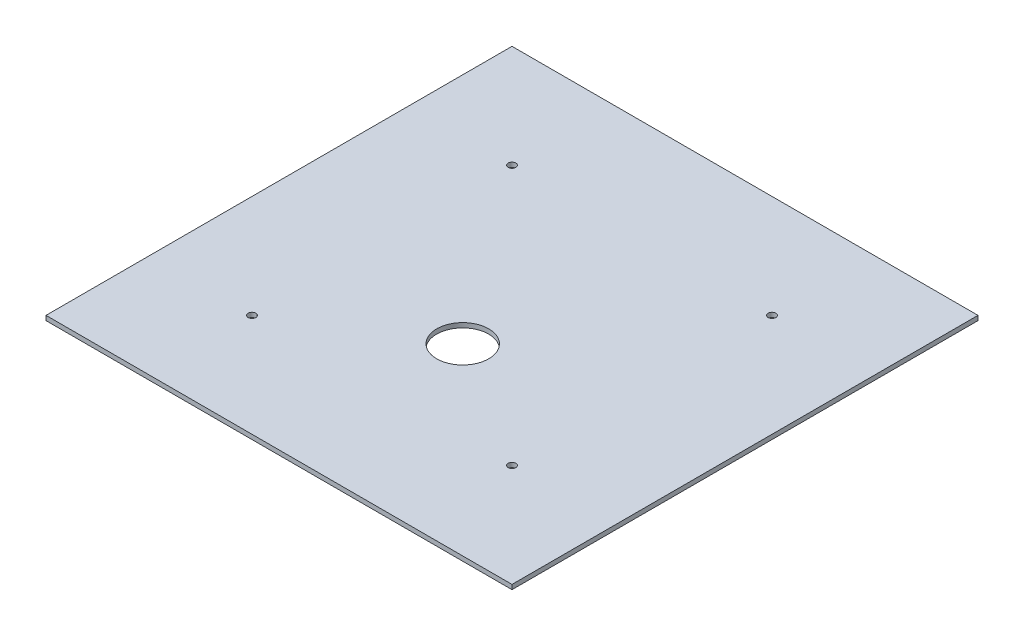
SolidWorks part; units mm, degrees
material "MDF"
ref_plane "Front Plane" through (0, 0, 0) normal (0, 0, 1) x (1, 0, 0)
ref_plane "Top Plane" through (0, 0, 0) normal (0, 1, 0) x (1, 0, 0)
ref_plane "Right Plane" through (0, 0, 0) normal (1, 0, 0) x (0, 0, -1)
sketch "Sketch2" plane through (0, 0, 0) normal (0, 1, 0) x (1, 0, 0)
  line L1 (-152.4, -152.4) -> (152.4, -152.4)
  line L2 (-152.4, -152.4) -> (-152.4, 152.4)
  line L3 (-152.4, 152.4) -> (152.4, 152.4)
  line L4 (152.4, -152.4) -> (152.4, 152.4)
  line L5 (-152.4, -152.4) -> (152.4, 152.4) construction
  line L6 (-152.4, 152.4) -> (152.4, -152.4) construction
  point P0 (0, 0)
  dimension "D1" = 304.8
  dimension "D2" = 304.8
extrude "Boss-Extrude1" add sketch "Sketch2" along normal blind 3
sketch "Sketch3" plane through (0, 3, 0) normal (0, 1, 0) x (1, 0, 0)
  line L0 (-85.035, 85.035) -> (85.035, 85.035) construction
  line L1 (85.035, 85.035) -> (85.035, -85.035) construction
  line L2 (85.035, -85.035) -> (-85.035, -85.035) construction
  line L3 (-85.035, -85.035) -> (-85.035, 85.035) construction
  line L4 (152.4, 152.4) -> (-152.4, 152.4) construction
  line L5 (152.4, -152.4) -> (152.4, 152.4) construction
  circle A4 centre (-85.035, 85.035) radius 2.5
  circle A5 centre (85.035, 85.035) radius 2.5
  circle A6 centre (-85.035, -85.035) radius 2.5
  circle A7 centre (85.035, -85.035) radius 2.5
  point P4 (0, 85.035)
  point P7 (0, 152.4)
  point P10 (152.4, 0)
  point P11 (85.035, 0)
  dimension "D3" = 5
  dimension "D2" = 170.07
extrude "Cut-Extrude1" cut sketch "Sketch3" against normal through all
sketch "Sketch4" plane through (0, 3, 0) normal (0, 1, 0) x (1, 0, 0)
  line L0 (0, -152.4) -> (0, 152.4) construction
  line L1 (-152.4, -152.4) -> (152.4, -152.4) construction
  line L2 (152.4, 152.4) -> (-152.4, 152.4) construction
  circle A0 centre (0, -32.24) radius 17
  dimension "D2" = 34
  dimension "D1" = 120.16
extrude "Cut-Extrude2" cut sketch "Sketch4" against normal through all
